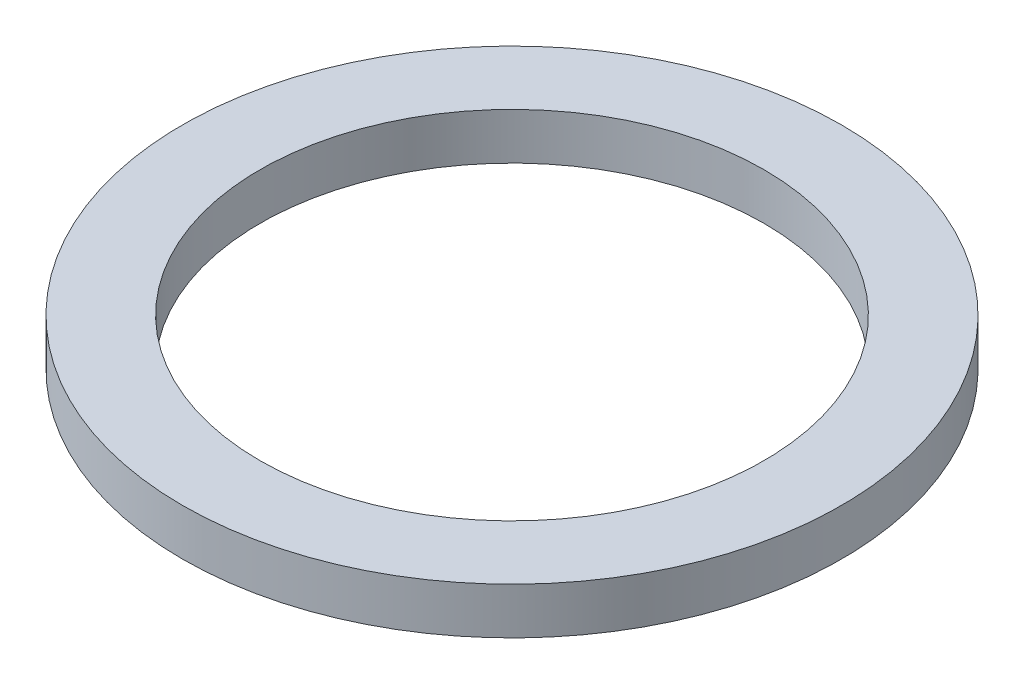
SolidWorks part; units mm, degrees
ref_plane "Plan de face" through (0, 0, 0) normal (0, 0, 1) x (1, 0, 0)
ref_plane "Plan de dessus" through (0, 0, 0) normal (0, 1, 0) x (1, 0, 0)
ref_plane "Plan de droite" through (0, 0, 0) normal (1, 0, 0) x (0, 0, -1)
sketch "Esquisse1" plane through (0, 0, 0) normal (0, 1, 0) x (1, 0, 0)
  circle A3 centre (0, 0) radius 3.25
  circle A4 centre (0, 0) radius 4.25
  dimension "D1" = 6.5
  dimension "D2" = 8.5
extrude "Boss.-Extru.1" add sketch "Esquisse1" along normal blind 0.6
